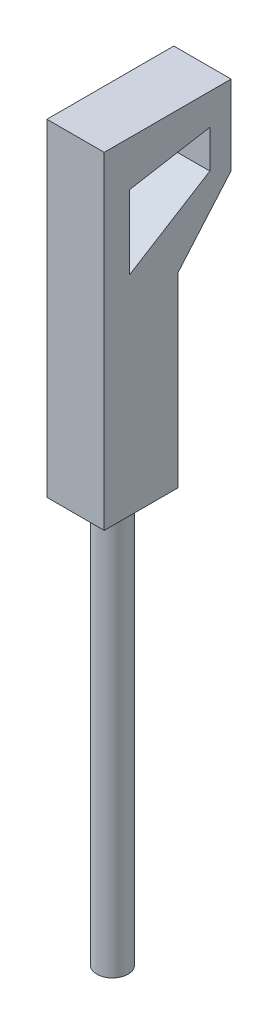
SolidWorks part; units mm, degrees
ref_plane "Front" through (0, 0, 0) normal (0, 0, 1) x (1, 0, 0)
ref_plane "Top" through (0, 0, 0) normal (0, 1, 0) x (1, 0, 0)
ref_plane "Right" through (0, 0, 0) normal (1, 0, 0) x (0, 0, -1)
sketch "Sketch2" plane through (0, 0, 0) normal (1, 0, 0) x (0, 0, -1)
  line L0 (0, 0) -> (155, 0)
  line L1 (155, 0) -> (155, -97.0479)
  line L2 (155, -97.0479) -> (90, -172.4249)
  line L3 (90, -172.4249) -> (90, -400)
  line L4 (90, -400) -> (0, -400)
  line L5 (0, -400) -> (0, 0)
  line L6 (31, -61.5) -> (129, -38)
  line L7 (129, -38) -> (129, -84.3232)
  line L8 (129, -84.3232) -> (89.6114, -130)
  line L9 (89.6114, -130) -> (31, -130)
  line L10 (31, -130) -> (31, -61.5)
  dimension "D2" = 28
  dimension "D3" = 155
  dimension "D5" = 400
  dimension "D6" = 61.5
  dimension "D7" = 38
  dimension "D8" = 26
  dimension "D10" = 130
  dimension "D11" = 31
  dimension "D12" = 90
extrude "Boss-Extrude1" add sketch "Sketch2" along normal blind 70 contours L5 L0 L1 L2 L3 L4
ref_plane "Plane1" through (35, 0, 0) normal (1, 0, 0) x (0, 0, -1)
sketch "Sketch3" plane through (70, 0, 0) normal (1, 0, 0) x (0, 0, -1)
  line L0 (31, -55) -> (129, -38)
  line L1 (129, -38) -> (129, -84.3232)
  line L2 (129, -84.3232) -> (31, -145)
  line L3 (31, -145) -> (31, -55)
  line L4 (0, 0) -> (155, 0) construction
  line L5 (155, 0) -> (155, -97.0479) construction
  line L6 (0, -400) -> (0, 0) construction
  line L9 (155, -97.0479) -> (90, -172.4249) construction
  dimension "D1" = 90
  dimension "D2" = 38
  dimension "D3" = 55
  dimension "D4" = 26
  dimension "D5" = 31
  dimension "D6" = 28
extrude "Cut-Extrude1" cut sketch "Sketch3" against normal through all both and the other way through all
sketch "Sketch4" plane through (0, -400, 0) normal (0, -1, 0) x (1, 0, 0)
  line L0 (0, 0) -> (70, -90) construction
  line L1 (0, -90) -> (70, 0) construction
  line L2 (0, -90) -> (0, 0) construction
  circle A0 centre (35, -45) radius 19.05
  dimension "D1" = 38.1
extrude "Boss-Extrude2" add sketch "Sketch4" along normal blind 500
ref_plane "Plane2" through (0, 0, -45) normal (0, 0, 1) x (1, 0, 0)
